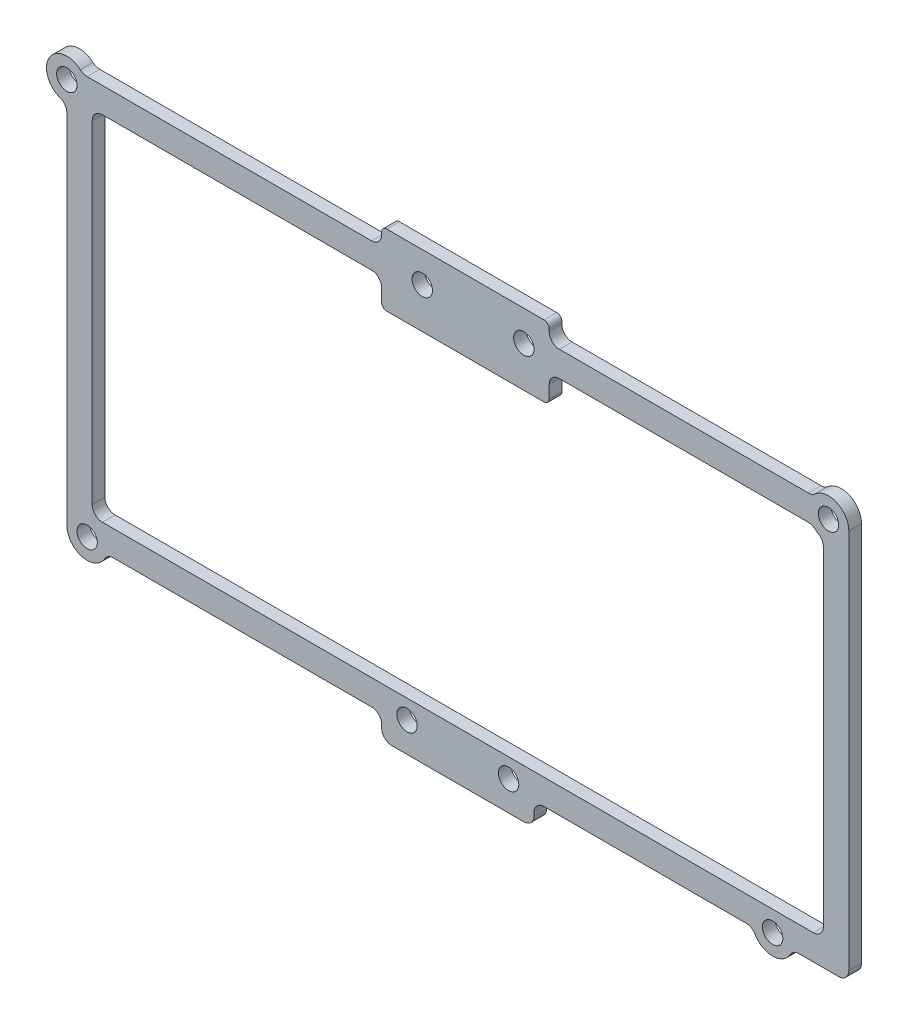
SolidWorks part; units mm, degrees
ref_plane "Front Plane" through (0, 0, 0) normal (0, 0, 1) x (1, 0, 0)
ref_plane "Top Plane" through (0, 0, 0) normal (0, 1, 0) x (1, 0, 0)
ref_plane "Right Plane" through (0, 0, 0) normal (1, 0, 0) x (0, 0, -1)
ref_plane "Plane1" through (0, 0, 0) normal (0, 0, -1) x (-1, 0, 0)
sketch "Sketch1" plane through (0, 0, 0) normal (0, 0, -1) x (-1, 0, 0)
  line L0 (-72.39, 378.46) -> (-72.39, 381.635)
  line L1 (-69.85, 384.175) -> (-2.54, 384.175)
  line L2 (0, 381.635) -> (0, 298.45)
  line L3 (-2.54, 295.91) -> (-180.34, 295.91)
  line L4 (-182.88, 298.45) -> (-182.88, 380.7509)
  line L5 (-179.1098, 384.175) -> (-116.84, 384.175)
  line L6 (-114.3, 381.635) -> (-114.3, 378.46)
  line L7 (-113.03, 377.19) -> (-73.66, 377.19)
  line L8 (-73.66, 394.97) -> (-113.03, 394.97)
  line L9 (-114.3, 393.7) -> (-114.3, 393.065)
  line L10 (-116.84, 390.525) -> (-179.1098, 390.525)
  line L11 (-189.23, 387.35) -> (-189.23, 292.1)
  line L12 (-186.69, 289.56) -> (-176.7791, 289.56)
  line L13 (-163.5809, 289.56) -> (-113.03, 289.56)
  line L14 (-110.49, 287.02) -> (-110.49, 286.258)
  line L15 (-107.95, 283.718) -> (-74.93, 283.718)
  line L16 (-72.39, 286.258) -> (-72.39, 287.02)
  line L17 (-69.85, 289.56) -> (-5.3291, 289.56)
  line L18 (6.35, 290.83) -> (6.35, 380.1658)
  line L19 (1.3098, 390.525) -> (-69.85, 390.525)
  line L20 (-72.39, 393.065) -> (-72.39, 393.7)
  circle A0 centre (-184.15, 387.35) radius 2.5527
  circle A1 centre (-107.95, 387.35) radius 2.5527
  circle A2 centre (-82.55, 387.35) radius 2.5527
  circle A3 centre (1.27, 290.83) radius 2.5527
  circle A4 centre (-104.14, 291.1475) radius 2.5527
  circle A5 centre (-78.74, 291.1475) radius 2.5527
  circle A6 centre (6.35, 387.35) radius 2.5527
  circle A7 centre (-170.18, 290.83) radius 2.5527
  arc A8 (-73.66, 377.19) -> (-72.39, 378.46) centre (-73.66, 378.46) ccw
  arc A9 (-72.39, 381.635) -> (-69.85, 384.175) centre (-69.85, 381.635) cw
  arc A10 (-2.54, 384.175) -> (0, 381.635) centre (-2.54, 381.635) cw
  arc A11 (0, 298.45) -> (-2.54, 295.91) centre (-2.54, 298.45) cw
  arc A12 (-180.34, 295.91) -> (-182.88, 298.45) centre (-180.34, 298.45) cw
  arc A13 (-182.88, 380.7509) -> (-181.61, 382.9506) centre (-180.34, 380.7509) cw
  arc A14 (-181.61, 382.9506) -> (-180.7899, 383.54) centre (-184.15, 387.35) ccw
  arc A15 (-180.7899, 383.54) -> (-179.1098, 384.175) centre (-179.1098, 381.635) cw
  arc A16 (-116.84, 384.175) -> (-114.3, 381.635) centre (-116.84, 381.635) cw
  arc A17 (-114.3, 378.46) -> (-113.03, 377.19) centre (-113.03, 378.46) ccw
  arc A18 (-72.39, 393.7) -> (-73.66, 394.97) centre (-73.66, 393.7) ccw
  arc A19 (-113.03, 394.97) -> (-114.3, 393.7) centre (-113.03, 393.7) ccw
  arc A20 (-114.3, 393.065) -> (-116.84, 390.525) centre (-116.84, 393.065) cw
  arc A21 (-179.1098, 390.525) -> (-180.7899, 391.16) centre (-179.1098, 393.065) cw
  arc A22 (-180.7899, 391.16) -> (-189.23, 387.35) centre (-184.15, 387.35) ccw
  arc A23 (-189.23, 292.1) -> (-186.69, 289.56) centre (-186.69, 292.1) ccw
  arc A24 (-176.7791, 289.56) -> (-174.5794, 288.29) centre (-176.7791, 287.02) cw
  arc A25 (-174.5794, 288.29) -> (-165.7806, 288.29) centre (-170.18, 290.83) ccw
  arc A26 (-165.7806, 288.29) -> (-163.5809, 289.56) centre (-163.5809, 287.02) cw
  arc A27 (-113.03, 289.56) -> (-110.49, 287.02) centre (-113.03, 287.02) cw
  arc A28 (-110.49, 286.258) -> (-107.95, 283.718) centre (-107.95, 286.258) ccw
  arc A29 (-74.93, 283.718) -> (-72.39, 286.258) centre (-74.93, 286.258) ccw
  arc A30 (-72.39, 287.02) -> (-69.85, 289.56) centre (-69.85, 287.02) cw
  arc A31 (-5.3291, 289.56) -> (-3.1294, 288.29) centre (-5.3291, 287.02) cw
  arc A32 (-3.1294, 288.29) -> (6.35, 290.83) centre (1.27, 290.83) ccw
  arc A33 (6.35, 380.1658) -> (8.0433, 382.5605) centre (8.89, 380.1658) cw
  arc A34 (8.0433, 382.5605) -> (2.9899, 391.16) centre (6.35, 387.35) ccw
  arc A35 (2.9899, 391.16) -> (1.3098, 390.525) centre (1.3098, 393.065) cw
  arc A36 (-69.85, 390.525) -> (-72.39, 393.065) centre (-69.85, 393.065) cw
extrude "Boss-Extrude1" add sketch "Sketch1" against normal blind 3.175
